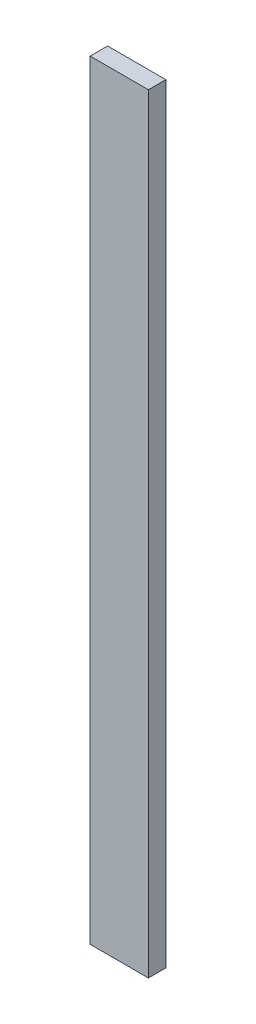
SolidWorks part; units mm, degrees
ref_plane "Front Plane" through (0, 0, 0) normal (0, 0, 1) x (1, 0, 0)
ref_plane "Top Plane" through (0, 0, 0) normal (0, 1, 0) x (1, 0, 0)
ref_plane "Right Plane" through (0, 0, 0) normal (1, 0, 0) x (0, 0, -1)
sketch "Sketch1" plane through (0, 0, 0) normal (0, 0, 1) x (1, 0, 0)
  line L0 (-49.142, 806.8248) -> (-49.142, -31.3752)
  line L1 (-49.142, -31.3752) -> (14.358, -31.3752)
  line L2 (-49.142, 806.8248) -> (14.358, 806.8248)
  line L3 (14.358, -31.3752) -> (14.358, 806.8248)
extrude "Boss-Extrude1" add sketch "Sketch1" along normal blind 19.05
